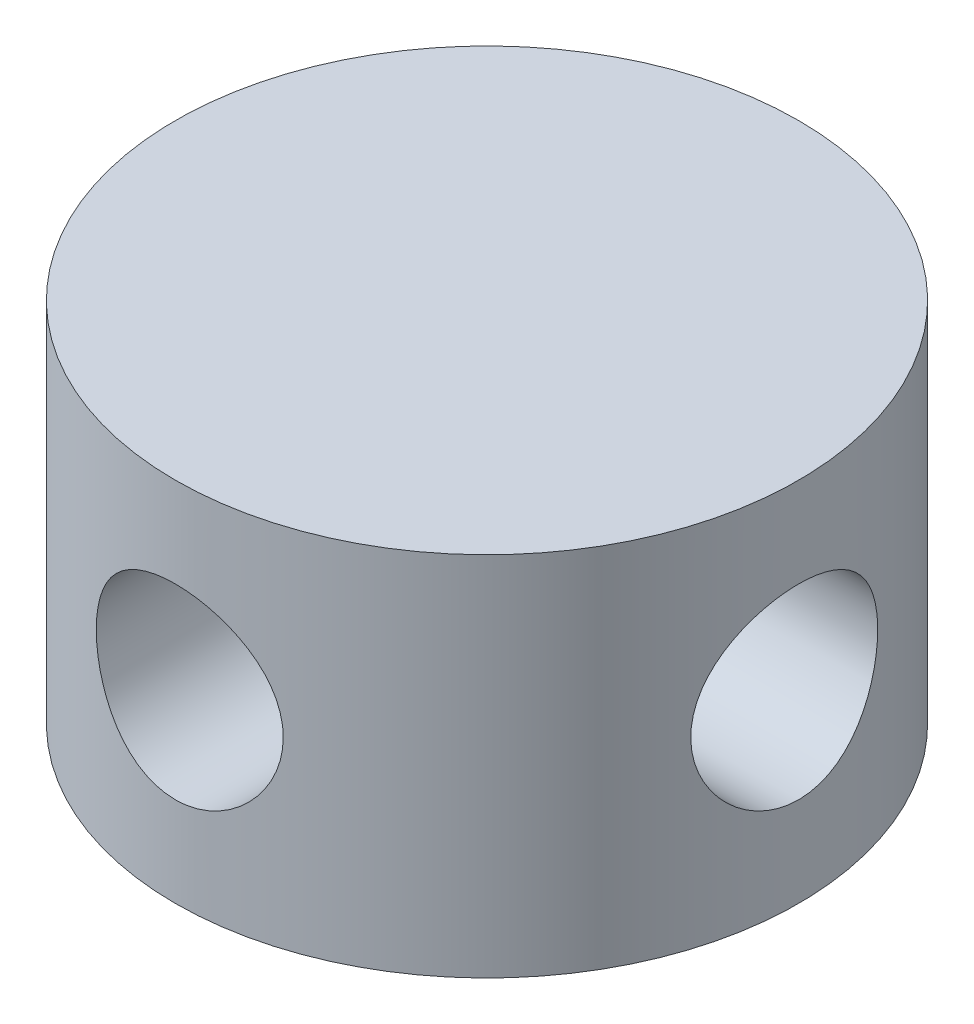
SolidWorks part; units mm, degrees
ref_plane "Front Plane" through (0, 0, 0) normal (0, 0, 1) x (1, 0, 0)
ref_plane "Top Plane" through (0, 0, 0) normal (0, 1, 0) x (1, 0, 0)
ref_plane "Right Plane" through (0, 0, 0) normal (1, 0, 0) x (0, 0, -1)
sketch "cirkel" plane through (0, 0, 0) normal (0, 1, 0) x (1, 0, 0)
  circle A0 centre (0, 0) radius 17
  dimension "D1" = 34
extrude "cilinder" add sketch "cirkel" along normal blind 20
ref_plane "Plane1" through (0, 0, 17) normal (0, 0, 1) x (1, 0, 0)
sketch "cirkel_gat" plane through (0, 0, 17) normal (0, 0, 1) x (1, 0, 0)
  line L0 (-17, 0) -> (17, 0) construction
  line L1 (0, 0) -> (0, 10) construction
  circle A0 centre (0, 10) radius 5.1
  dimension "D1" = 10.2
  dimension "D2" = 10
extrude "opening" cut sketch "cirkel_gat" against normal blind 10 contours A0
pattern_circular "gaten_patroon" count 4 over 360 about axis through (0, 0, 0) along (0, 1, 0) of "opening"
sketch "cirkel1" plane through (0, 0, 0) normal (0, -1, 0) x (-1, 0, 0)
  circle A0 centre (0, 0) radius 13.5
  dimension "D1" = 27
extrude "opening_opzet" cut sketch "cirkel1" against normal blind 3
sketch "cirkel2" plane through (0, 3, 0) normal (0, -1, 0) x (-1, 0, 0)
  circle A0 centre (0, 0) radius 1.9
  dimension "D1" = 3.8
extrude "gat_verloopstuk" cut sketch "cirkel2" against normal blind 8
sketch "cirkel3" plane through (0, 3, 0) normal (0, -1, 0) x (1, 0, 0)
  circle A0 centre (0, 0) radius 2.9
  dimension "D1" = 5.8
extrude "gat_verloopstuk_rand" cut sketch "cirkel3" against normal blind 2
